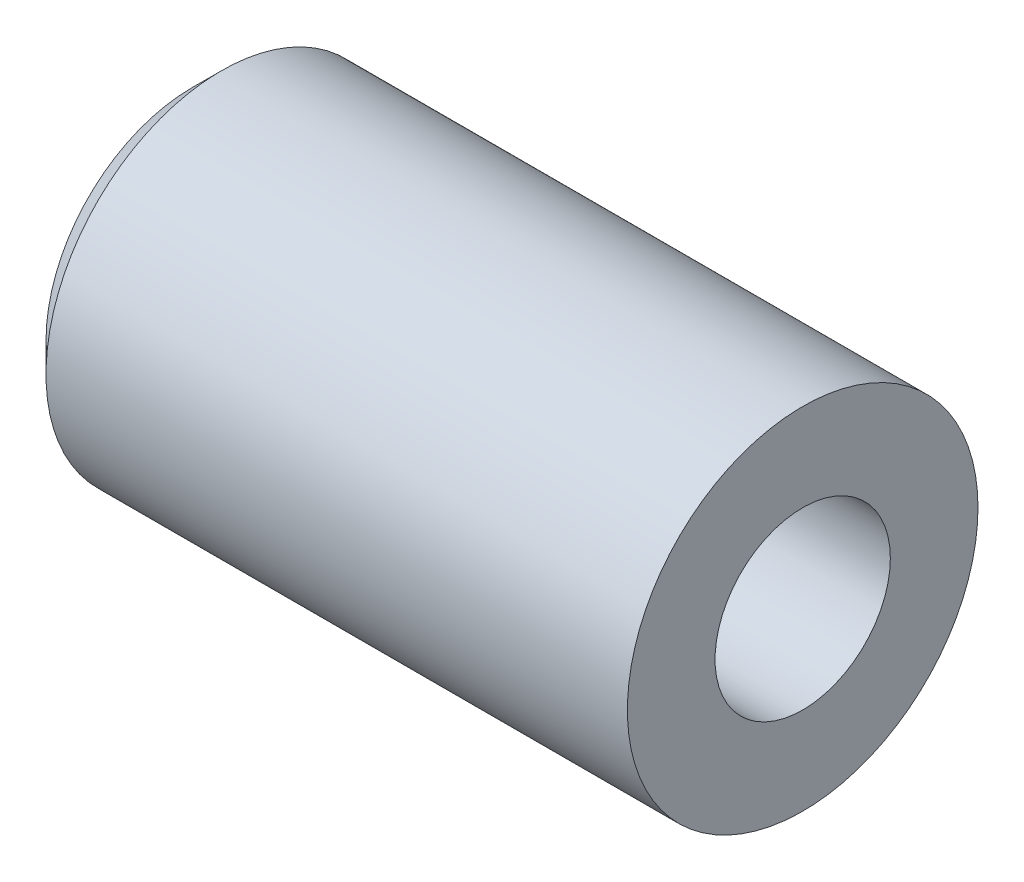
SolidWorks part; units mm, degrees
material "PA Type 6"
ref_plane "Front Plane" through (0, 0, 0) normal (0, 0, 1) x (1, 0, 0)
ref_plane "Top Plane" through (0, 0, 0) normal (0, 1, 0) x (1, 0, 0)
ref_plane "Right Plane" through (0, 0, 0) normal (1, 0, 0) x (0, 0, -1)
sketch "Sketch1" plane through (0, 0, 0) normal (1, 0, 0) x (0, 0, -1)
  circle A0 centre (0, 0) radius 6
  circle A1 centre (0, 0) radius 3
  dimension "D1" = 12
  dimension "D2" = 6
extrude "Boss-Extrude1" add sketch "Sketch1" along normal blind 20.9
chamfer "Chamfer1" distance 1 angle 45 1 edges at (0, 0, -6)
move or copy body "Body-Move/Copy1" [suppressed] bodies to move or copy 101
